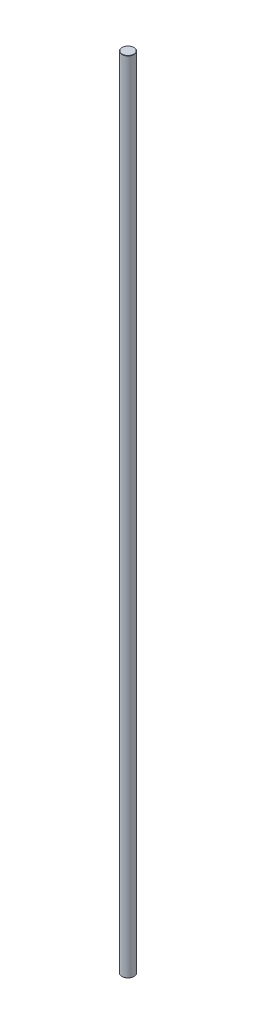
SolidWorks part; units mm, degrees
material "Plain Carbon Steel"
ref_plane "Front Plane" through (0, 0, 0) normal (0, 0, 1) x (1, 0, 0)
ref_plane "Top Plane" through (0, 0, 0) normal (0, 1, 0) x (1, 0, 0)
ref_plane "Right Plane" through (0, 0, 0) normal (1, 0, 0) x (0, 0, -1)
sketch "Sketch1" plane through (0, 0, 0) normal (0, 1, 0) x (1, 0, 0)
  circle A0 centre (0, 0) radius 6.35
  dimension "D1" = 12.7
extrude "Boss-Extrude1" add sketch "Sketch1" along normal mid plane 838.2
chamfer "Chamfer1" distance 0.254 angle 45 2 edges at (0, -419.1, 6.35) (0, 419.1, 6.35)
